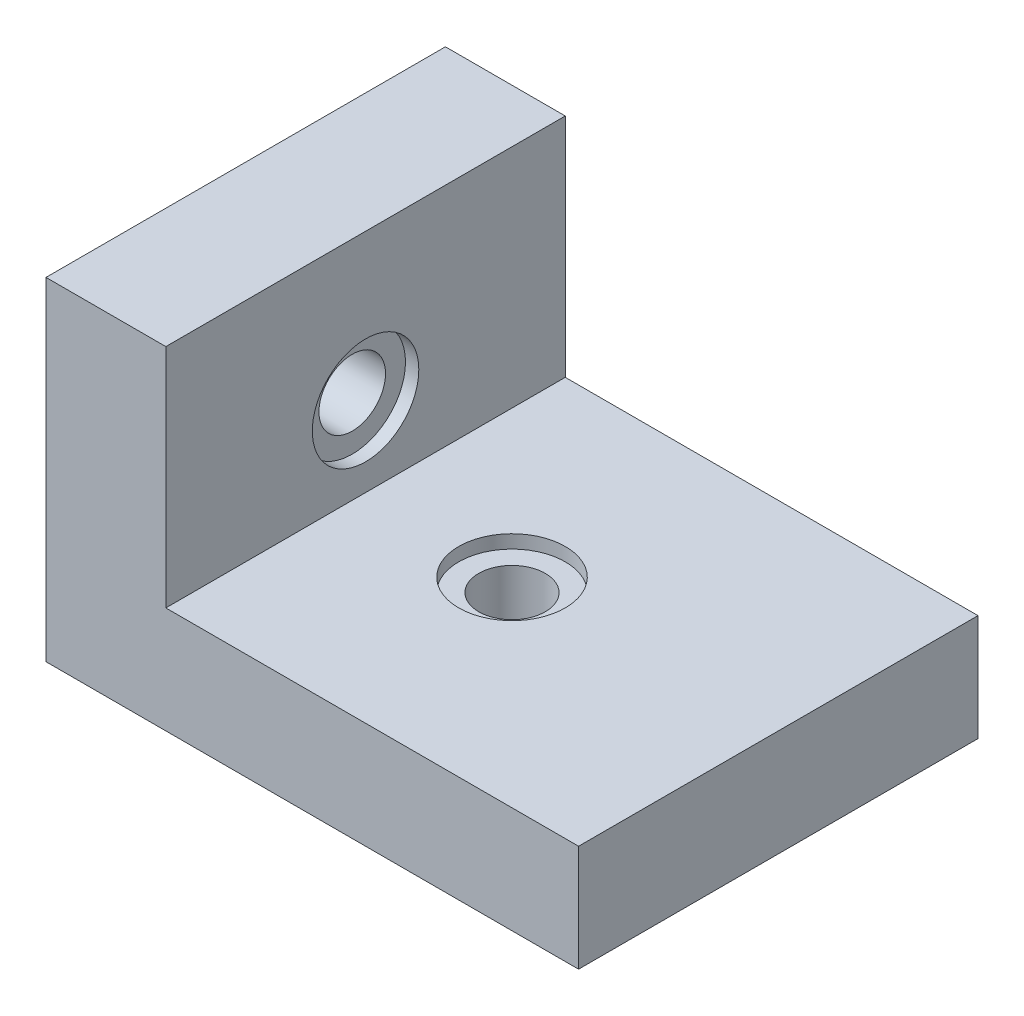
SolidWorks part; units mm, degrees
ref_plane "정면" through (0, 0, 0) normal (0, 0, 1) x (1, 0, 0)
ref_plane "윗면" through (0, 0, 0) normal (0, 1, 0) x (1, 0, 0)
ref_plane "우측면" through (0, 0, 0) normal (1, 0, 0) x (0, 0, -1)
sketch "스케치3" plane through (0, 0, 0) normal (0, 1, 0) x (1, 0, 0)
  line L1 (0, 0) -> (40, 0)
  line L2 (0, 0) -> (0, -30)
  line L3 (0, -30) -> (40, -30)
  line L4 (40, 0) -> (40, -30)
  circle A0 centre (20, -15) radius 2.5
  point P8 (0, -15)
  dimension "D3" = 5
  dimension "D1" = 40
  dimension "D2" = 30
  dimension "D4" = 20
extrude "보스-돌출3" add sketch "스케치3" along normal blind 8
sketch "스케치4" plane through (0, 0, 0) normal (1, 0, 0) x (0, 0, -1)
  line L5 (-30, 0) -> (0, 0)
  line L6 (-30, 0) -> (-30, 25)
  line L7 (-30, 25) -> (0, 25)
  line L8 (0, 0) -> (0, 25)
  circle A0 centre (-15, 14) radius 2.5
  point P8 (-15, 0)
  dimension "D3" = 5
  dimension "D1" = 30
  dimension "D2" = 25
  dimension "D4" = 14
extrude "보스-돌출4" add sketch "스케치4" along normal blind 9
sketch "스케치5" plane through (0, 8, 0) normal (0, 1, 0) x (1, 0, 0)
  circle A0 centre (20, -15) radius 4
  dimension "D1" = 8
extrude "컷-돌출1" cut sketch "스케치5" against normal blind 1
sketch "스케치6" plane through (9, 0, 0) normal (1, 0, 0) x (0, 0, -1)
  circle A0 centre (-15, 14) radius 4
  dimension "D1" = 8
extrude "컷-돌출2" cut sketch "스케치6" against normal blind 1
